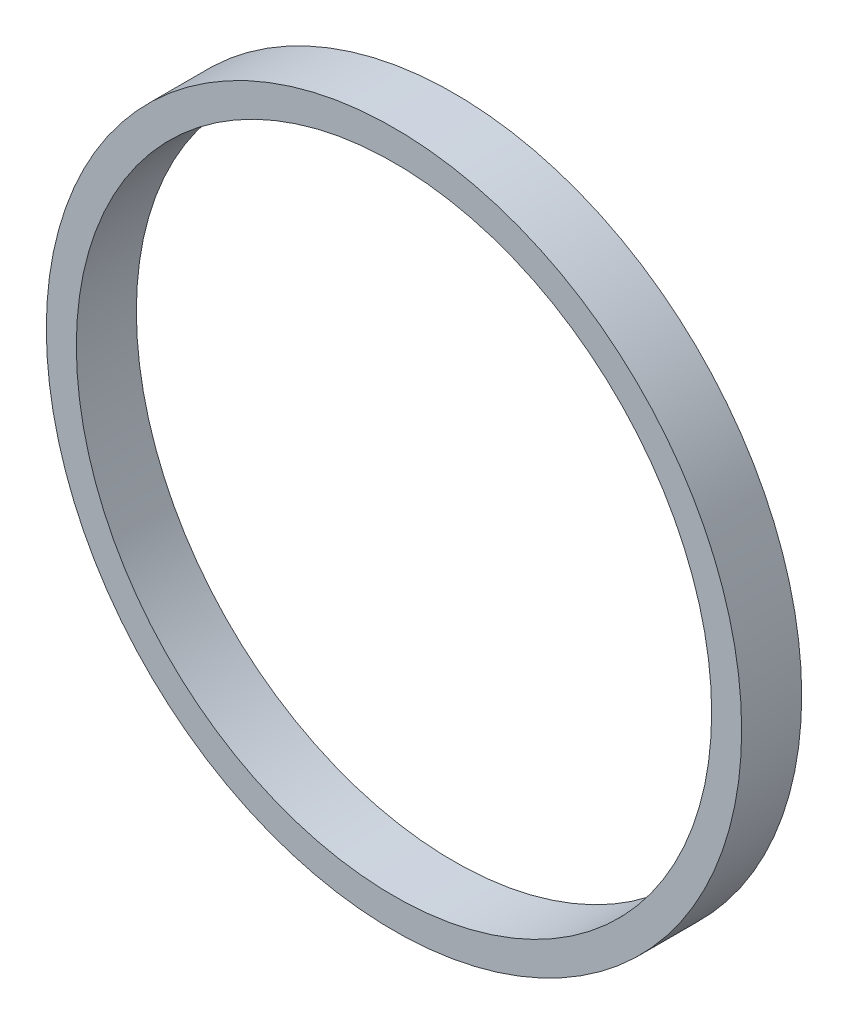
SolidWorks part; units mm, degrees
ref_plane "Front Plane" through (0, 0, 0) normal (0, 0, 1) x (1, 0, 0)
ref_plane "Top Plane" through (0, 0, 0) normal (0, 1, 0) x (1, 0, 0)
ref_plane "Right Plane" through (0, 0, 0) normal (1, 0, 0) x (0, 0, -1)
sketch "Sketch2" plane through (0, 0, 0) normal (0, 0, 1) x (1, 0, 0)
  circle A0 centre (0, 0) radius 44.1325
  dimension "D1" = 88.265
extrude "Boss-Extrude2" add sketch "Sketch2" along normal blind 7.62 contours A0
sketch "Sketch3" plane through (0, 0, 0) normal (0, 0, -1) x (-1, 0, 0)
  circle A0 centre (0, 0) radius 40.3225
  dimension "D1" = 80.645
extrude "Cut-Extrude1" cut sketch "Sketch3" against normal blind 7.62
sketch "Sketch4" plane through (0, 0, 0) normal (0, 0, -1) x (-1, 0, 0)
  line L0 (0, 0) -> (0, 40.3225) construction
  line L1 (2.4232, 40.3225) -> (-2.4232, 40.3225)
  line L2 (-2.4232, 40.3225) -> (-2.4232, 41.6644)
  line L3 (-2.4232, 41.6644) -> (2.4232, 41.6644)
  line L4 (2.4232, 41.6644) -> (2.4232, 40.3225)
  circle A0 centre (0, 0) radius 40.3225 construction
  point P9 (0, 40.3225)
  dimension "D1" = 4.8464
